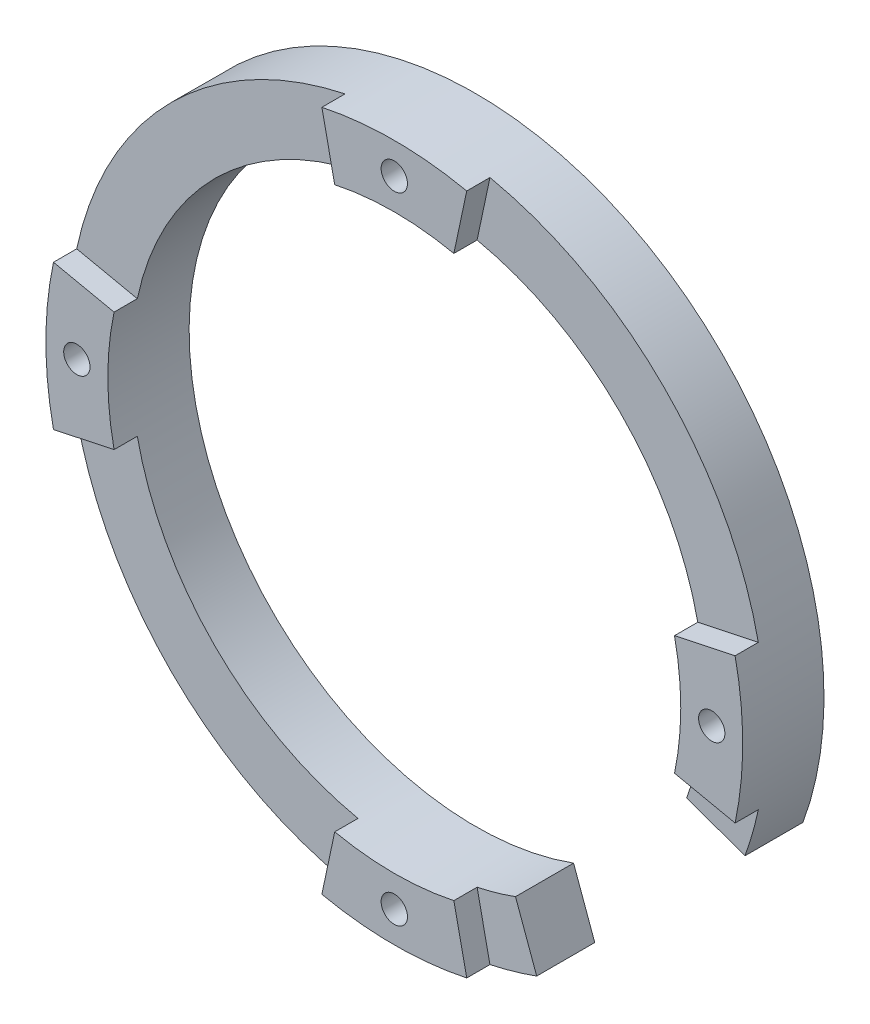
SolidWorks part; units mm, degrees
ref_plane "前视基准面" through (0, 0, 0) normal (0, 0, 1) x (1, 0, 0)
ref_plane "上视基准面" through (0, 0, 0) normal (0, 1, 0) x (1, 0, 0)
ref_plane "右视基准面" through (0, 0, 0) normal (1, 0, 0) x (0, 0, -1)
sketch "草图1" plane through (0, 0, 0) normal (0, 0, 1) x (1, 0, 0)
  circle A0 centre (0, 0) radius 45
  circle A1 centre (0, 0) radius 37
  circle A2 centre (41, 0) radius 1.7
  circle A3 centre (0, -41) radius 1.7
  circle A4 centre (-41, 0) radius 1.7
  circle A5 centre (0, 41) radius 1.7
  circle A6 centre (0, 0) radius 41 construction
  point P17 (0, 0)
  dimension "D1" = 90
  dimension "D2" = 74
  dimension "D3" = 3.4
  dimension "D5" = 82
  dimension "D4" = 4
extrude "凸台-拉伸1" add sketch "草图1" along normal blind 10.5
sketch "草图2" plane through (0, 0, 10.5) normal (0, 0, 1) x (1, 0, 0)
  line L0 (0, 0) -> (9.356, 44.0166) construction
  line L1 (0, 0) -> (44.0166, 9.356) construction
  line L2 (0, 0) -> (39.3, 0) construction
  line L3 (0, 0) -> (0, 42.7) construction
  line L4 (9.356, 44.0166) -> (7.6927, 36.1915)
  line L5 (44.0166, 9.356) -> (36.1915, 7.6927)
  circle A0 centre (0, 0) radius 37 construction
  circle A1 centre (0, 0) radius 45 construction
  arc A2 (36.1915, 7.6927) -> (7.6927, 36.1915) centre (0, 0) ccw
  arc A3 (44.0166, 9.356) -> (9.356, 44.0166) centre (0, 0) ccw
  circle A4 centre (41, 0) radius 1.7 construction
  circle A5 centre (0, 41) radius 1.7 construction
  dimension "D1" = 12
  dimension "D2" = 12
extrude "切除-拉伸1" cut sketch "草图2" against normal blind 3
pattern_circular "阵列(圆周)1" count 4 over 360 about axis through (0, 0, 10.5) along (0, 0, -1) of "切除-拉伸1"
sketch "草图3" plane through (0, 0, 7.5) normal (0, 0, 1) x (1, 0, 0)
  line L0 (34.7686, -12.6547) -> (42.2862, -15.3909)
  line L1 (12.6547, -34.7686) -> (15.3909, -42.2862)
  line L2 (44.0166, -9.356) -> (36.1915, -7.6927)
  line L3 (7.6927, -36.1915) -> (9.356, -44.0166)
  line L6 (7.6927, -36.1915) -> (9.356, -44.0166) construction
  line L7 (44.0166, -9.356) -> (36.1915, -7.6927) construction
  arc A2 (9.356, -44.0166) -> (44.0166, -9.356) centre (0, 0) ccw
  arc A3 (7.6927, -36.1915) -> (36.1915, -7.6927) centre (0, 0) ccw
  arc A4 (15.3909, -42.2862) -> (42.2862, -15.3909) centre (0, 0) ccw
  arc A5 (12.6547, -34.7686) -> (34.7686, -12.6547) centre (0, 0) ccw
  dimension "D2" = 8
  dimension "D3" = 172
  dimension "D1" = 0
extrude "切除-拉伸2" cut sketch "草图3" against normal blind 13
